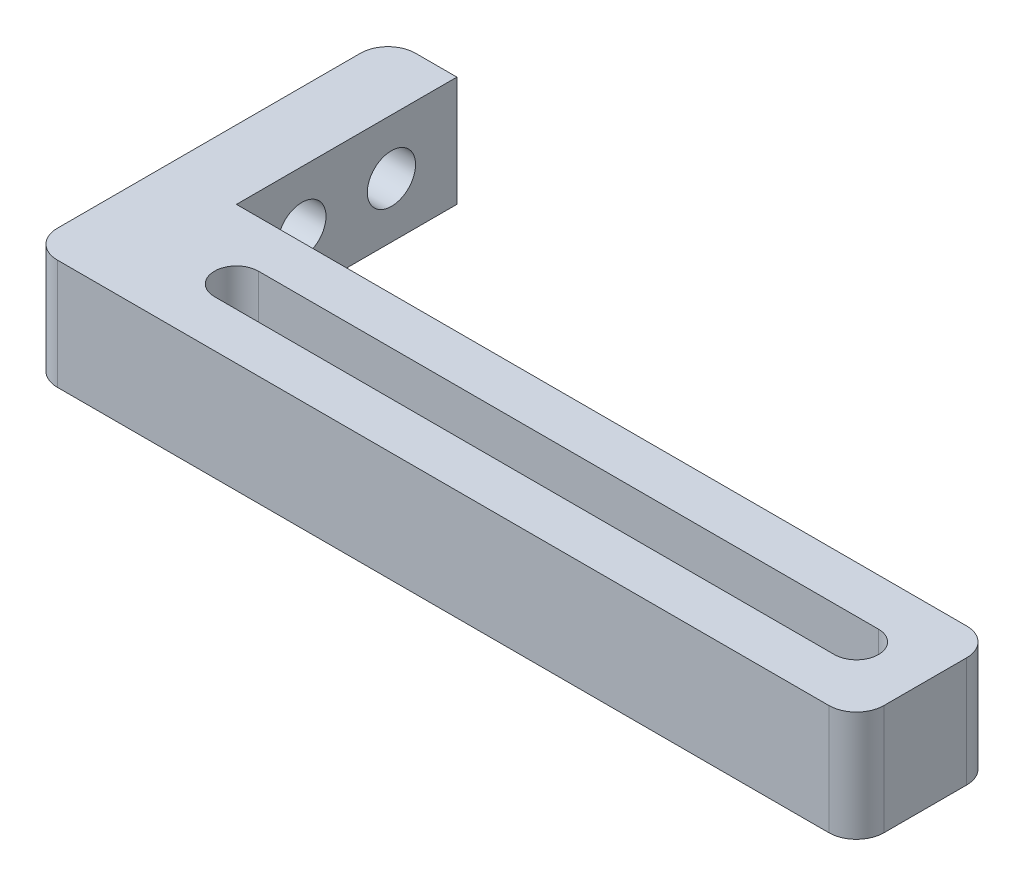
SolidWorks part; units mm, degrees
ref_plane "Front Plane" through (0, 0, 0) normal (0, 0, 1) x (1, 0, 0)
ref_plane "Top Plane" through (0, 0, 0) normal (0, 1, 0) x (1, 0, 0)
ref_plane "Right Plane" through (0, 0, 0) normal (1, 0, 0) x (0, 0, -1)
sketch "Sketch1" plane through (0, 0, 0) normal (0, 1, 0) x (1, 0, 0)
  line L0 (0, 26) -> (0, 0)
  line L1 (0, 0) -> (60, 0)
  line L2 (60, 0) -> (60, 10)
  line L3 (60, 10) -> (5, 10)
  line L4 (5, 10) -> (5, 26)
  line L5 (5, 26) -> (0, 26)
  dimension "D1" = 60
  dimension "D2" = 16
  dimension "D3" = 5
  dimension "D4" = 10
extrude "Boss-Extrude1" add sketch "Sketch1" along normal blind 8
sketch "Sketch2" plane through (5, 0, 0) normal (1, 0, 0) x (0, 0, -1)
  line L0 (21.25, 4) -> (14.75, 4) construction
  line L3 (21.25, 4) -> (26, 4) construction
  line L4 (26, 8) -> (26, 0) construction
  circle A0 centre (21.25, 4) radius 1.75
  circle A1 centre (14.75, 4) radius 1.75
  point P2 (21.2069, 4)
  dimension "D2" = 3.5
  dimension "D1" = 6.5
  dimension "D3" = 4.75
extrude "Cut-Extrude1" cut sketch "Sketch2" against normal through all
sketch "Sketch3" plane through (0, 8, 0) normal (0, 1, 0) x (1, 0, 0)
  line L0 (10, 5) -> (55, 5) construction
  line L1 (10, 6.6) -> (55, 6.6)
  line L2 (10, 3.4) -> (55, 3.4)
  line L3 (55, 5) -> (60, 5) construction
  line L4 (60, 0) -> (60, 10) construction
  line L5 (5, 10) -> (5, 26) construction
  arc A0 (10, 6.6) -> (10, 3.4) centre (10, 5) ccw
  arc A1 (55, 3.4) -> (55, 6.6) centre (55, 5) ccw
  point P2 (32.5, 5)
  point P9 (45, 15)
  dimension "D1" = 3.2
  dimension "D2" = 45
  dimension "D3" = 5
extrude "Cut-Extrude2" cut sketch "Sketch3" against normal through all
sketch "Sketch4" plane through (0, 0, 0) normal (0, -1, 0) x (1, 0, 0)
  line L0 (55, -5) -> (10, -5) construction
  line L1 (55, -7.85) -> (10, -7.85)
  line L2 (55, -2.15) -> (10, -2.15)
  arc A0 (55, -7.85) -> (55, -2.15) centre (55, -5) ccw
  arc A1 (10, -2.15) -> (10, -7.85) centre (10, -5) ccw
  point P4 (32.5, -5)
  dimension "D1" = 5.7
extrude "Cut-Extrude3" cut sketch "Sketch4" against normal blind 3
fillet "Fillet1" radius 2 4 edges at (0, 4, -26) (0, 4, 0) (60, 4, 0) (60, 4, -10)
